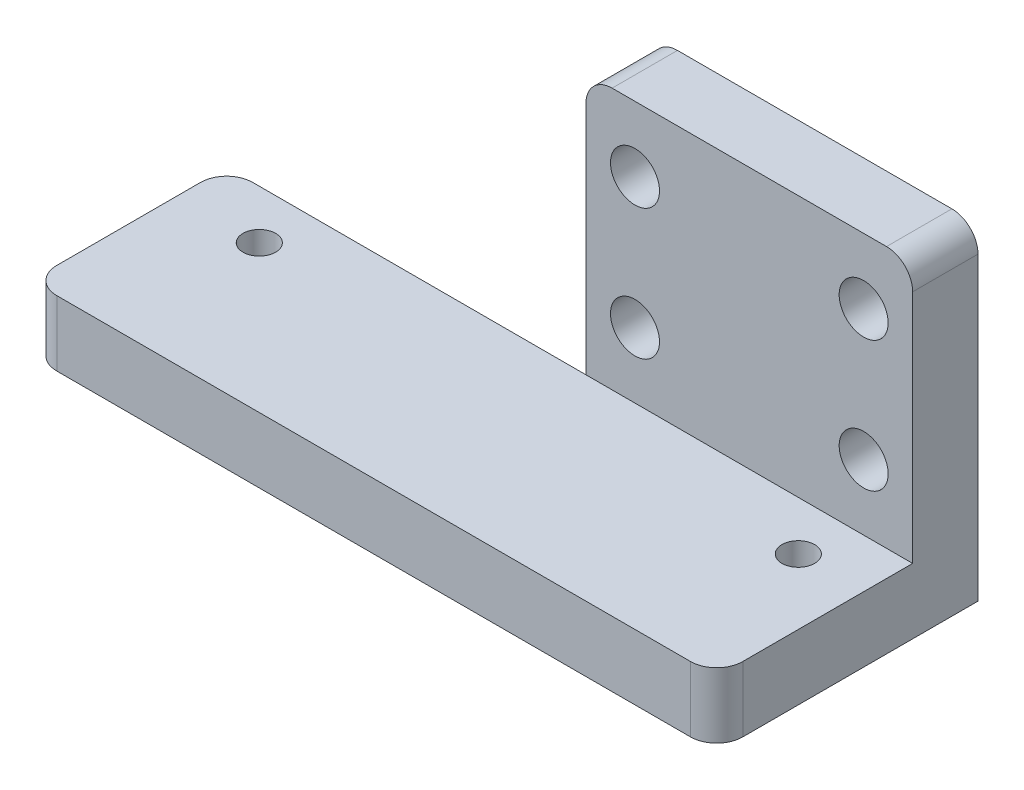
SolidWorks part; units mm, degrees
ref_plane "Front Plane" through (0, 0, 0) normal (0, 0, 1) x (1, 0, 0)
ref_plane "Top Plane" through (0, 0, 0) normal (0, 1, 0) x (1, 0, 0)
ref_plane "Right Plane" through (0, 0, 0) normal (1, 0, 0) x (0, 0, -1)
sketch "Sketch1" plane through (0, 0, 0) normal (0, 0, 1) x (1, 0, 0)
  line L1 (-15.875, -15.875) -> (15.875, -15.875)
  line L2 (-15.875, -15.875) -> (-15.875, 15.875)
  line L3 (-15.875, 15.875) -> (15.875, 15.875)
  line L4 (15.875, -15.875) -> (15.875, 15.875)
  line L5 (-15.875, -15.875) -> (15.875, 15.875) construction
  line L6 (-15.875, 15.875) -> (15.875, -15.875) construction
  circle A0 centre (-11.1125, -3.175) radius 2.3813
  circle A1 centre (-11.1125, 9.525) radius 2.3813
  circle A2 centre (11.1125, 9.525) radius 2.3813
  circle A3 centre (11.1125, -3.175) radius 2.3813
  point P0 (0, 0)
  dimension "D3" = 4.7625
  dimension "D4" = 4.7625
  dimension "D10" = 4.7625
  dimension "D11" = 4.7625
  dimension "D1" = 31.75
  dimension "D2" = 31.75
  dimension "D5" = 12.7
  dimension "D6" = 12.7
  dimension "D7" = 4.7625
  dimension "D8" = 12.7
  dimension "D9" = 12.7
  dimension "D12" = 4.7625
extrude "Boss-Extrude1" add sketch "Sketch1" along normal blind 6.35
sketch "Sketch2" plane through (0, 0, 6.35) normal (0, 0, 1) x (1, 0, 0)
  line L1 (-50.8, -15.875) -> (15.875, -15.875)
  line L2 (-50.8, -15.875) -> (-50.8, -9.525)
  line L3 (-50.8, -9.525) -> (15.875, -9.525)
  line L4 (15.875, -15.875) -> (15.875, -9.525)
  dimension "D1" = 66.675
  dimension "D2" = 6.35
extrude "Boss-Extrude2" add sketch "Sketch2" along normal blind 19.05
sketch "Sketch3" plane through (0, -9.525, 0) normal (0, 1, 0) x (1, 0, 0)
  line L0 (15.875, -25.4) -> (15.875, -6.35) construction
  line L1 (-15.875, -6.35) -> (-50.8, -6.35) construction
  circle A0 centre (9.525, -11.1125) radius 1.5875
  circle A1 centre (-42.8625, -11.1125) radius 1.5875
  dimension "D1" = 3.175
  dimension "D3" = 6.35
  dimension "D5" = 3.175
  dimension "D2" = 4.7625
  dimension "D4" = 52.3875
extrude "Cut-Extrude1" cut sketch "Sketch3" against normal through all
fillet "Fillet1" radius 2.54 5 edges at (15.875, 15.875, 3.175) (-15.875, 15.875, 3.175) (-50.8, -12.7, 25.4) (-50.8, -12.7, 6.35) (15.875, -12.7, 25.4)
